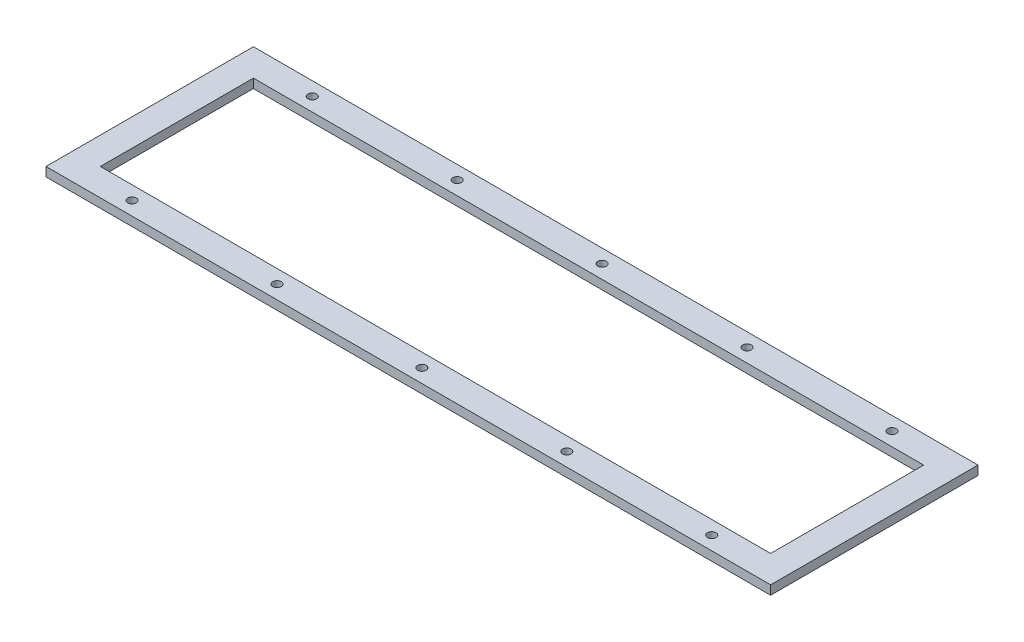
SolidWorks part; units mm, degrees
ref_plane "Front Plane" through (0, 0, 0) normal (0, 0, 1) x (1, 0, 0)
ref_plane "Top Plane" through (0, 0, 0) normal (0, 1, 0) x (1, 0, 0)
ref_plane "Right Plane" through (0, 0, 0) normal (1, 0, 0) x (0, 0, -1)
sketch "Sketch1" plane through (0, 0, 0) normal (0, 1, 0) x (1, 0, 0)
  line L0 (3.175, 3.175) -> (3.175, 69.5249) construction
  line L1 (0, 0) -> (254, 0)
  line L2 (0, 0) -> (0, 72.6999)
  line L3 (0, 72.6999) -> (254, 72.6999)
  line L4 (254, 0) -> (254, 72.6999)
  line L5 (6.35, 66.3499) -> (194.85, 66.3499) construction
  line L6 (6.35, 66.3499) -> (6.35, 6.35) construction
  line L7 (6.35, 6.35) -> (194.85, 6.35) construction
  line L8 (194.85, 66.3499) -> (194.85, 6.35) construction
  line L9 (3.175, 69.5249) -> (250.825, 69.5249) construction
  line L10 (250.825, 3.175) -> (250.825, 69.5249) construction
  line L11 (3.175, 3.175) -> (250.825, 3.175) construction
  line L12 (562.1369, 340.2788) -> (1927.4703, 340.2788) construction
  line L13 (3.175, 3.175) -> (3.175, 69.5249) construction
  line L28 (127, 72.6999) -> (127, 0) construction
  line L29 (127, 69.5249) -> (127, 66.3499) construction
  line L30 (0, 36.3499) -> (254, 36.3499) construction
  line L32 (6.35, 66.284) -> (6.35, 6.35) construction
  line L33 (6.35, 6.35) -> (194.851, 6.35) construction
  line L34 (194.851, 66.284) -> (194.851, 6.35) construction
  line L35 (9.525, 63.1749) -> (244.475, 63.1749)
  line L52 (-1511.8018, 332.3966) -> (-146.4685, 332.3966) construction
  line L54 (244.475, 63.1749) -> (244.475, 9.525)
  line L55 (244.475, 9.525) -> (9.525, 9.525)
  line L56 (9.525, 63.1749) -> (9.525, 9.525)
  line L57 (244.475, 63.1749) -> (9.525, 9.525) construction
  line L58 (244.475, 9.525) -> (9.525, 63.1749) construction
  line L65 (127, 67.9374) -> (177.8, 67.9374) construction
  circle A0 centre (177.8, 67.9374) radius 1.5
  circle A1 centre (177.8, 4.7625) radius 1.5
  circle A2 centre (228.6, 67.9374) radius 1.5
  circle A3 centre (228.6, 4.7625) radius 1.5
  circle A4 centre (214.0118, 59.3649) radius 3.81 construction
  circle A15 centre (127, 67.9374) radius 1.5
  circle A20 centre (127, 4.7625) radius 1.5
  circle A21 centre (25.4, 4.7625) radius 1.5
  circle A22 centre (76.2, 4.7625) radius 1.5
  circle A23 centre (25.4, 67.9374) radius 1.5
  circle A24 centre (76.2, 67.9374) radius 1.5
  point P33 (127, 36.3499)
  point P48 (127, 67.9374)
  dimension "D6" = 3.175
  dimension "D11" = 7.62
  dimension "D13" = 188.5
  dimension "D15" = 3
  dimension "D1" = 59.9999
  dimension "D2" = 3.175
  dimension "D3" = 3.175
  dimension "D4" = 3.175
  dimension "D5" = 3.175
  dimension "D7" = 3.175
  dimension "D8" = 3.175
  dimension "D9" = 19.1618
  dimension "D10" = 10.16
  dimension "D12" = 72.6999
  dimension "D14" = 254
  dimension "D16" = 3
  dimension "D17" = 50.8
  dimension "D26" = 3.175
  dimension "D27" = 9.525
  dimension "D29" = 9.525
  dimension "D30" = 9.525
  dimension "D32" = 9.525
extrude "Boss-Extrude1" add sketch "Sketch1" against normal blind 3.175
